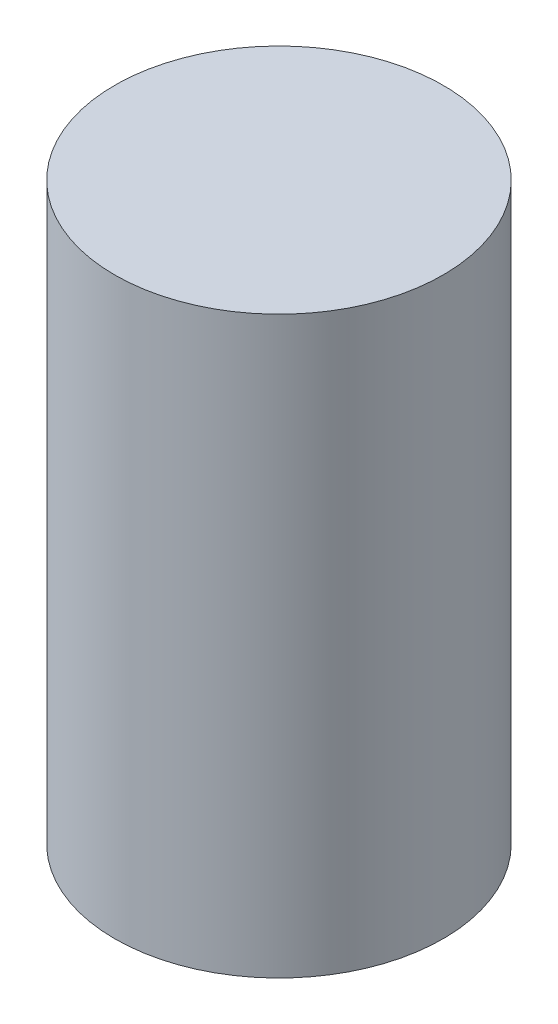
SolidWorks part; units mm, degrees
ref_plane "Front Plane" through (0, 0, 0) normal (0, 0, 1) x (1, 0, 0)
ref_plane "Top Plane" through (0, 0, 0) normal (0, 1, 0) x (1, 0, 0)
ref_plane "Right Plane" through (0, 0, 0) normal (1, 0, 0) x (0, 0, -1)
sketch "Sketch2" plane through (0, 0, 0) normal (0, 1, 0) x (1, 0, 0)
  circle A0 centre (-33.7559, 30.1569) radius 2
extrude "Boss-Extrude1" add sketch "Sketch2" along normal blind 7
